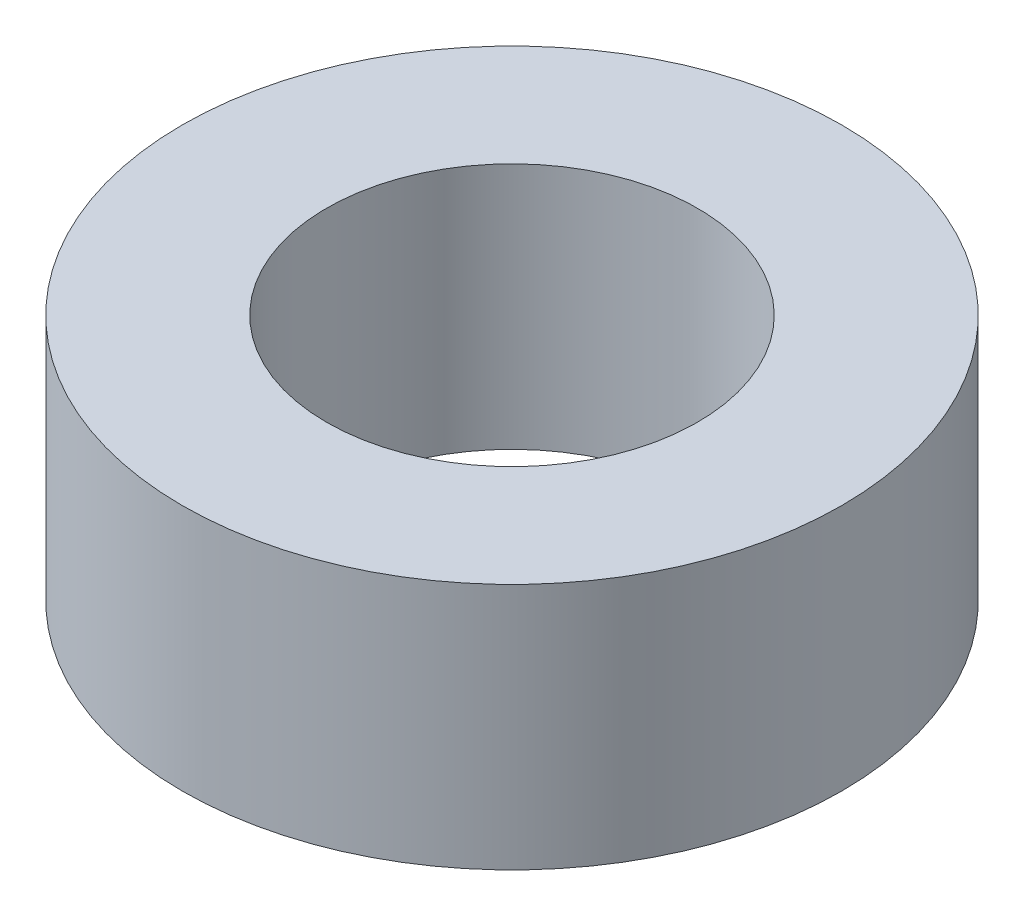
SolidWorks part; units mm, degrees
material "ABS"
ref_plane "Спереди" through (0, 0, 0) normal (0, 0, 1) x (1, 0, 0)
ref_plane "Сверху" through (0, 0, 0) normal (0, 1, 0) x (1, 0, 0)
ref_plane "Справа" through (0, 0, 0) normal (1, 0, 0) x (0, 0, -1)
sketch "Эскиз1" plane through (0, 0, 0) normal (0, 1, 0) x (1, 0, 0)
  circle A0 centre (0, 0) radius 2.25
  circle A1 centre (0, 0) radius 4
  dimension "D1" = 4.5
  dimension "D2" = 8
extrude "Бобышка-Вытянуть1" add sketch "Эскиз1" along normal blind 3
